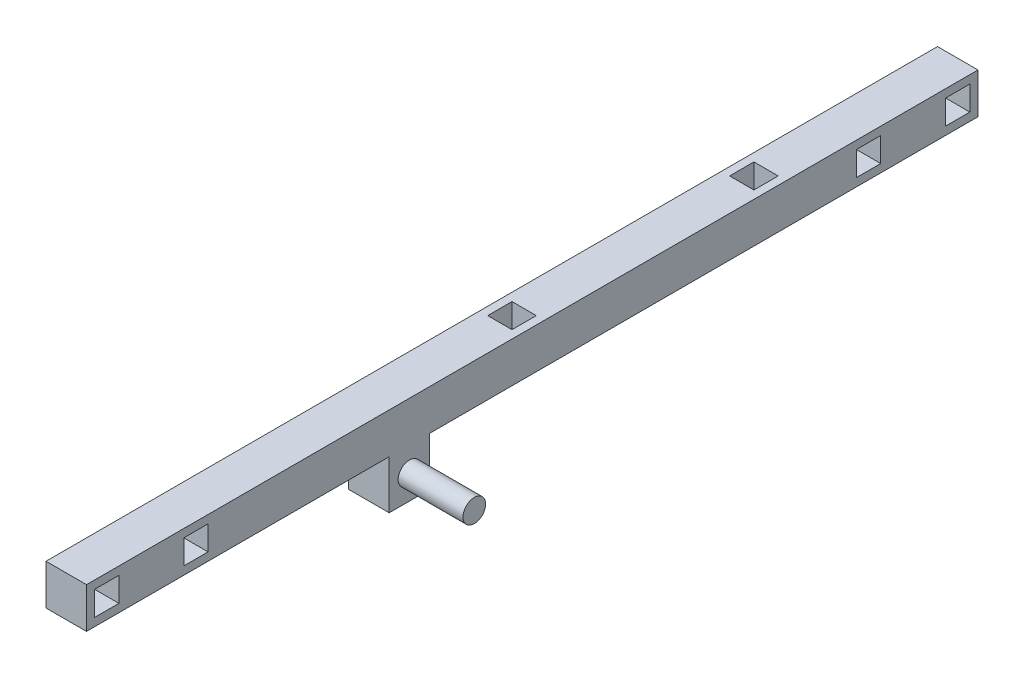
SolidWorks part; units mm, degrees
ref_plane "Front Plane" through (0, 0, 0) normal (0, 0, 1) x (1, 0, 0)
ref_plane "Top Plane" through (0, 0, 0) normal (0, 1, 0) x (1, 0, 0)
ref_plane "Right Plane" through (0, 0, 0) normal (1, 0, 0) x (0, 0, -1)
sketch "Sketch1" plane through (0, 0, 0) normal (0, 0, 1) x (1, 0, 0)
  line L1 (0, 0) -> (5, 0)
  line L2 (0, 0) -> (0, 5)
  line L3 (0, 5) -> (5, 5)
  line L4 (5, 0) -> (5, 5)
  dimension "D1" = 5
  dimension "D2" = 5
extrude "Boss-Extrude1" add sketch "Sketch1" along normal blind 110
sketch "Sketch2" plane through (0, 0, 0) normal (-1, 0, 0) x (0, 0, 1)
  line L0 (0, 5) -> (0, 0) construction
  line L1 (1, 1) -> (4, 1)
  line L2 (1, 1) -> (1, 4)
  line L3 (1, 4) -> (4, 4)
  line L4 (4, 1) -> (4, 4)
  line L5 (110, 5) -> (0, 5) construction
  line L6 (110, 5) -> (110, 0) construction
  line L7 (109, 4) -> (106, 4)
  line L8 (109, 4) -> (109, 1)
  line L9 (109, 1) -> (106, 1)
  line L10 (106, 4) -> (106, 1)
  line L12 (12, 4) -> (15, 4)
  line L13 (12, 4) -> (12, 1)
  line L14 (12, 1) -> (15, 1)
  line L15 (15, 4) -> (15, 1)
  line L16 (95, 4) -> (98, 4)
  line L17 (95, 4) -> (95, 1)
  line L18 (95, 1) -> (98, 1)
  line L19 (98, 4) -> (98, 1)
  dimension "D1" = 3
  dimension "D2" = 3
  dimension "D3" = 1
  dimension "D4" = 1
  dimension "D5" = 3
  dimension "D6" = 3
  dimension "D7" = 1
  dimension "D8" = 1
  dimension "D9" = 3
  dimension "D10" = 3
  dimension "D11" = 1
  dimension "D12" = 12
  dimension "D13" = 3
  dimension "D14" = 3
  dimension "D15" = 1
  dimension "D16" = 12
extrude "Cut-Extrude1" cut sketch "Sketch2" against normal blind 9
sketch "Sketch3" plane through (0, 5, 0) normal (0, 1, 0) x (1, 0, 0)
  line L0 (0, -110) -> (0, 0) construction
  line L1 (1, -23.65) -> (4, -23.65)
  line L2 (1, -23.65) -> (1, -26.65)
  line L3 (1, -26.65) -> (4, -26.65)
  line L4 (4, -23.65) -> (4, -26.65)
  line L5 (1, -26.65) -> (4, -23.65) construction
  line L6 (1, -23.65) -> (4, -26.65) construction
  line L7 (5, 0) -> (0, 0) construction
  line L9 (1, -53.5) -> (4, -53.5)
  line L10 (1, -53.5) -> (1, -56.5)
  line L11 (1, -56.5) -> (4, -56.5)
  line L12 (4, -53.5) -> (4, -56.5)
  point P6 (2.5, -25.15)
  point P13 (1, -55)
  dimension "D1" = 3
  dimension "D2" = 3
  dimension "D3" = 1
  dimension "D4" = 4.2426
  dimension "D5" = 4.2426
  dimension "D6" = 25.15
  dimension "D7" = 3
  dimension "D8" = 3
  dimension "D9" = 1
  dimension "D10" = 53.5
extrude "Cut-Extrude2" cut sketch "Sketch3" against normal blind 9
sketch "Sketch4" plane through (0, 0, 0) normal (0, -1, 0) x (-1, 0, 0)
  line L0 (-5, -110) -> (-5, 0) construction
  line L1 (-5, -67.65) -> (0, -67.65)
  line L2 (-5, -67.65) -> (-5, -72.65)
  line L3 (-5, -72.65) -> (0, -72.65)
  line L4 (0, -67.65) -> (0, -72.65)
  line L5 (0, -110) -> (0, 0) construction
  line L6 (-5, -72.65) -> (0, -67.65) construction
  line L7 (-5, -67.65) -> (0, -72.65) construction
  line L8 (-4, -26.65) -> (-1, -23.65) construction
  line L9 (-4, -23.65) -> (-1, -26.65) construction
  point P20 (-2.5, -25.15)
  point P21 (-2.5, -70.15)
  dimension "D1" = 5
  dimension "D2" = 7.0711
  dimension "D3" = 7.0711
  dimension "D4" = 4.2426
  dimension "D5" = 4.2426
  dimension "D6" = 45
extrude "Boss-Extrude2" add sketch "Sketch4" along normal blind 6
sketch "Sketch5" plane through (0, 0, 0) normal (-1, 0, 0) x (0, 0, 1)
  line L0 (72.65, -6) -> (72.65, 0) construction
  line L1 (110, 0) -> (72.65, 0) construction
  circle A0 centre (70.15, -3) radius 1.4
  dimension "D1" = 2.8
  dimension "D2" = 2.5
  dimension "D3" = 3
extrude "Boss-Extrude3" add sketch "Sketch5" against normal blind 13
